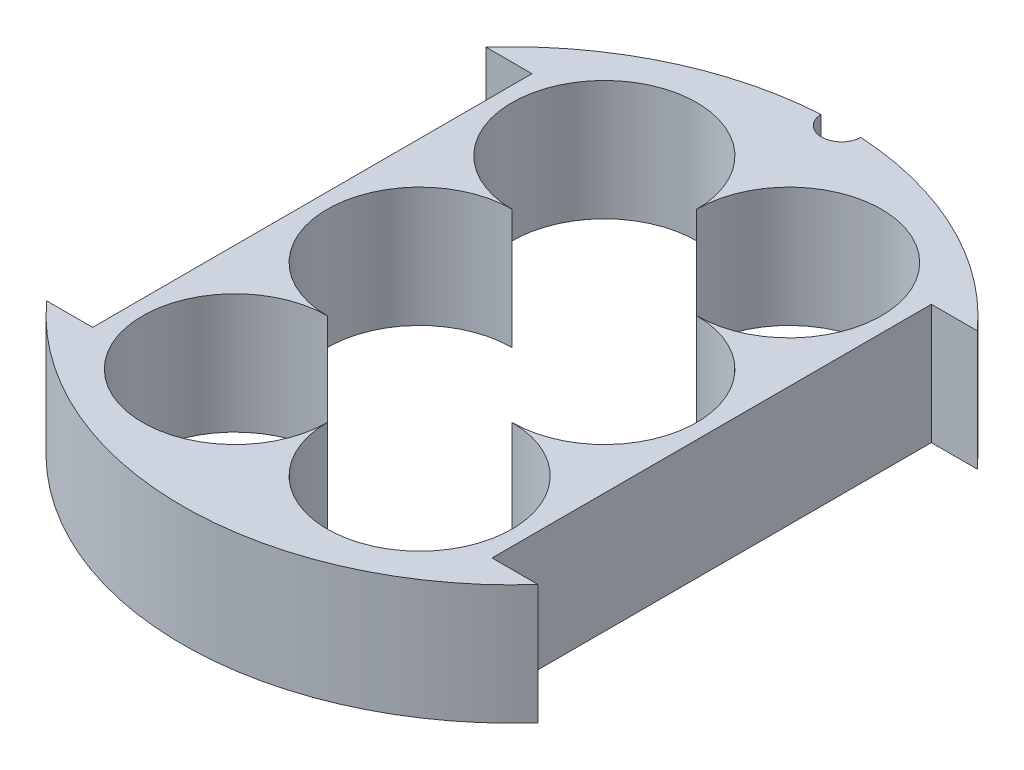
SolidWorks part; units mm, degrees
ref_plane "Ön Düzlem" through (0, 0, 0) normal (0, 0, 1) x (1, 0, 0)
ref_plane "Üst Düzlem" through (0, 0, 0) normal (0, 1, 0) x (1, 0, 0)
ref_plane "Sağ Düzlem" through (0, 0, 0) normal (1, 0, 0) x (0, 0, -1)
sketch "Çizim1" plane through (0, 0, 0) normal (0, 1, 0) x (1, 0, 0)
  line L0 (0, 0) -> (20, 0)
  line L1 (0, 0) -> (-20, 0)
  line L5 (20, -22) -> (20, 22)
  line L6 (0, 18.5) -> (9.25, 18.5)
  line L7 (0, 18.5) -> (-9.25, 18.5)
  line L8 (20, -22) -> (24.5967, -22)
  line L9 (20, 22) -> (24.5967, 22)
  line L10 (-20, 22) -> (-20, -22)
  line L13 (-20, -22) -> (-24.5967, -22)
  line L15 (-24.5967, 22) -> (-20, 22)
  arc A0 (24.5967, 22) -> (1.9991, 32.9394) centre (0, 0) ccw
  arc A7 (0, 18.5) -> (-9.25, 9.25) centre (-9.25, 18.5) ccw
  arc A8 (9.25, 9.25) -> (0, 18.5) centre (9.25, 18.5) ccw
  arc A9 (-9.25, 9.25) -> (-9.25, -9.25) centre (-9.25, 0) ccw
  arc A10 (9.25, -9.25) -> (9.25, 9.25) centre (9.25, 0) ccw
  arc A11 (-9.25, -9.25) -> (0, -18.5) centre (-9.25, -18.5) ccw
  arc A12 (0, -18.5) -> (9.25, -9.25) centre (9.25, -18.5) ccw
  arc A13 (-24.5967, -22) -> (24.5967, -22) centre (0, 0) ccw
  arc A14 (-1.9991, 32.9394) -> (1.9991, 32.9394) centre (0, 33) ccw
  arc A15 (-1.9991, 32.9394) -> (-24.5967, 22) centre (0, 0) ccw
  point P20 (0, 0)
  dimension "D5" = 9.25
  dimension "D4" = 9.25
extrude "Yükseklik-Ekstrüzyon1" add sketch "Çizim1" along normal blind 12 contours L13 A13 L8 L5 L0 A10 A12 A11 A9 L1 L10 | A14 A15 L15 L10 L1 A9 A7 A8 A10 L0 L5 L9 A0
